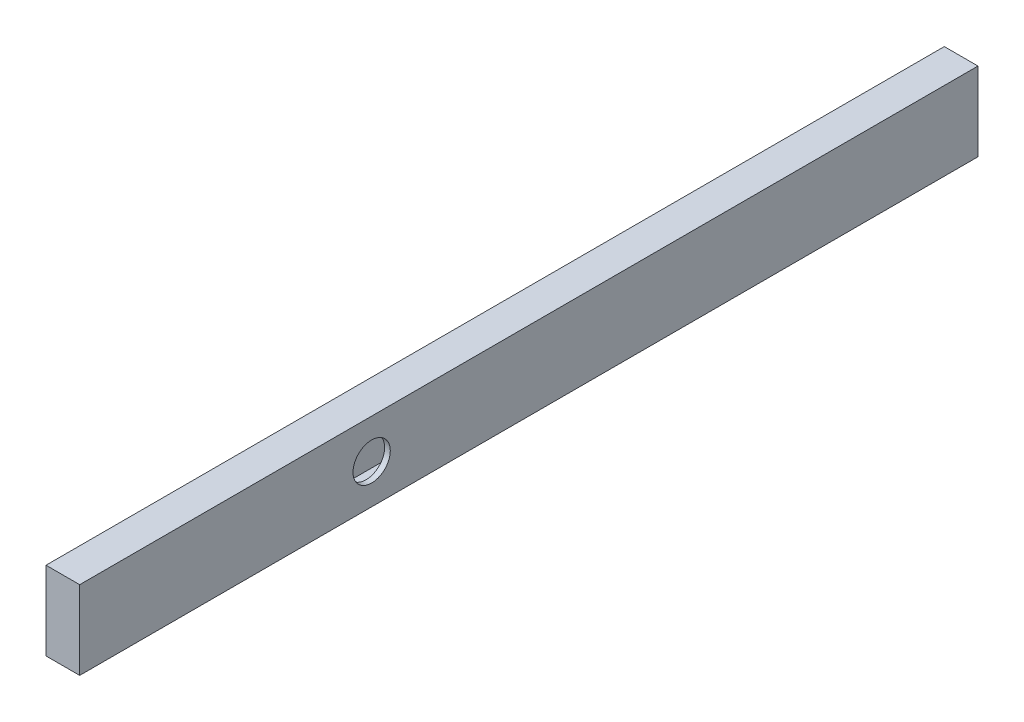
SolidWorks part; units mm, degrees
ref_plane "Front Plane" through (0, 0, 0) normal (1, 0, 0) x (0, 1, 0)
ref_plane "Top Plane" through (0, 0, 0) normal (0, 0, 1) x (0, 1, 0)
ref_plane "Right Plane" through (0, 0, 0) normal (0, 1, 0) x (-1, 0, 0)
sketch "Sketch1" plane through (0, 0, 0) normal (0, 0, 1) x (0, 1, 0)
  line L1 (-44.45, -19.05) -> (44.45, -19.05)
  line L2 (-44.45, -19.05) -> (-44.45, 19.05)
  line L3 (-44.45, 19.05) -> (44.45, 19.05)
  line L4 (44.45, -19.05) -> (44.45, 19.05)
  line L5 (-44.45, -19.05) -> (44.45, 19.05) construction
  line L6 (-44.45, 19.05) -> (44.45, -19.05) construction
  point P0 (0, 0)
  dimension "D1" = 88.9
  dimension "D2" = 38.1
extrude "Boss-Extrude1" add sketch "Sketch1" along normal blind 1016
shell "Shell1" thickness 6.35
sketch "Sketch2" plane through (19.05, 0, 0) normal (1, 0, 0) x (0, 1, 0)
  point P0 (0, 685.8)
  point P1 (0, 0)
  dimension "D1" = 685.8
hole_wizard "5/16 (1.66) Diameter Hole1" positions "Sketch2" profile "Sketch3" hole size "5/16" standard "ANSI Inch" end condition through all
sketch "Sketch3" plane through (19.05, 0, 685.8) normal (0, 1, 0) x (0, 0, -1)
  line L0 (0, 0) -> (0, 38.1)
  line L1 (0, 38.1) -> (21.082, 38.1)
  line L2 (21.082, 38.1) -> (21.082, 0)
  line L5 (21.082, 0) -> (0, 0)
  line L11 (0, -6.35) -> (0, 107.95) construction
  dimension "Thru Hole Dia." = 42.164
  dimension "Thru Hole Depth" = 38.1
